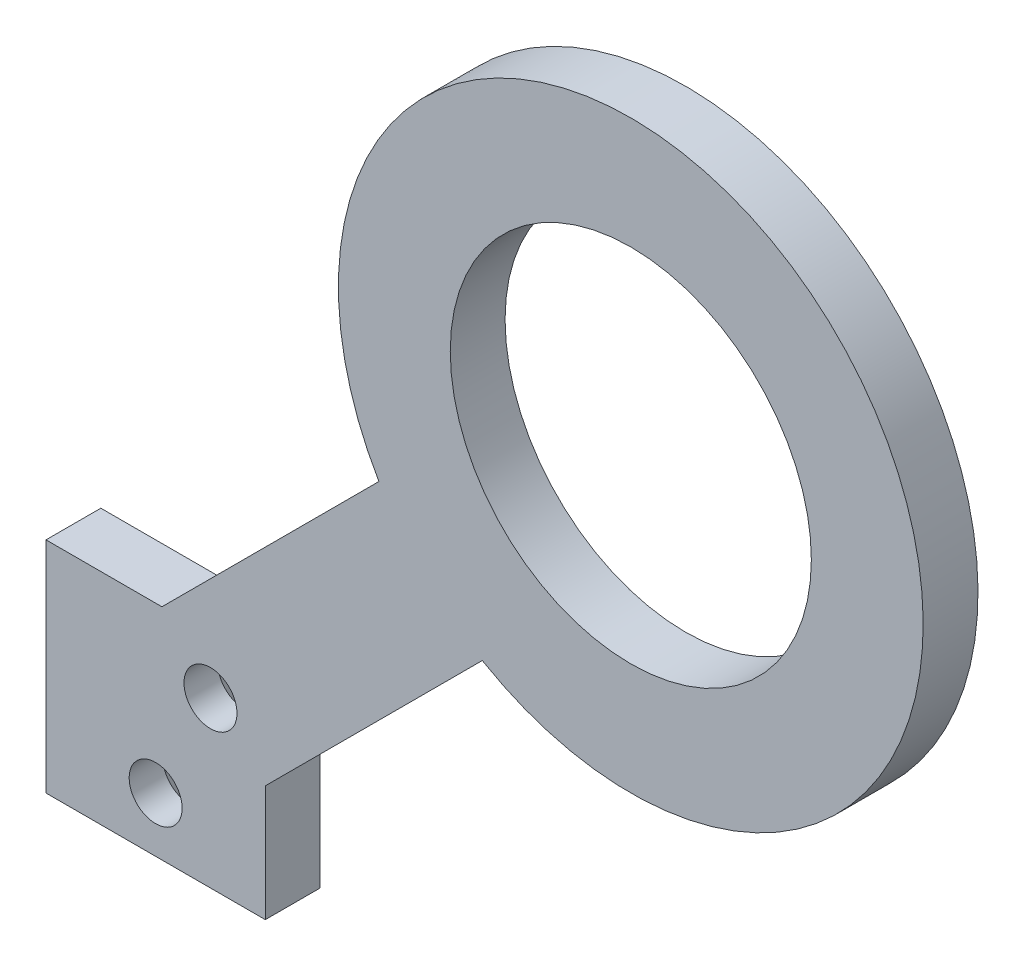
SolidWorks part; units mm, degrees
ref_plane "Front Plane" through (0, 0, 0) normal (0, 0, 1) x (1, 0, 0)
ref_plane "Top Plane" through (0, 0, 0) normal (0, 1, 0) x (1, 0, 0)
ref_plane "Right Plane" through (0, 0, 0) normal (1, 0, 0) x (0, 0, -1)
sketch "Sketch1" plane through (0, 0, 0) normal (0, 0, 1) x (1, 0, 0)
  circle A0 centre (50, 50) radius 16
  circle A1 centre (50, 50) radius 9.88
extrude "Stop_Ring_D19p76_OD32" add sketch "Sketch1" along normal blind 3 from offset 3
sketch "Sketch2" plane through (0, 0, 0) normal (0, 0, 1) x (1, 0, 0)
  line L0 (21.1716, 26.8284) -> (37.6716, 43.3284)
  line L1 (37.6716, 43.3284) -> (43.3284, 37.6716)
  line L2 (43.3284, 37.6716) -> (26.8284, 21.1716)
  line L3 (26.8284, 21.1716) -> (21.1716, 26.8284)
extrude "Outboard_Bridge" add sketch "Sketch2" along normal blind 3 from offset 3
sketch "Sketch3" plane through (0, 0, 0) normal (0, 0, 1) x (1, 0, 0)
  line L1 (18, 18) -> (30, 18)
  line L2 (18, 18) -> (18, 30)
  line L3 (18, 30) -> (30, 30)
  line L4 (30, 18) -> (30, 30)
extrude "Base_Attachment_Pad" add sketch "Sketch3" along normal blind 3 from offset 3
sketch "Sketch5" plane through (0, 0, -3) normal (0, 0, -1) x (-1, 0, 0)
  circle A0 centre (-21, 21) radius 1.45
  circle A1 centre (-27, 27) radius 1.45
sketch "Sketch6" plane through (0, 0, -3) normal (0, 0, -1) x (-1, 0, 0)
  circle A0 centre (-21, 21) radius 2.6
  circle A1 centre (-27, 27) radius 2.6
sketch "Sketch7" plane through (0, 0, -3) normal (0, 0, -1) x (-1, 0, 0)
  circle A0 centre (-21, 21) radius 2.6
  circle A1 centre (-27, 27) radius 2.6
sketch "Sketch8" plane through (0, 0, -3) normal (0, 0, -1) x (-1, 0, 0)
  circle A0 centre (-24, 21) radius 1.45
  circle A1 centre (-27, 27) radius 1.45
extrude "Stop_Mount_D2p9_Through" cut sketch "Sketch8" against normal blind 3.01
sketch "Sketch9" plane through (0, 0, -3) normal (0, 0, -1) x (-1, 0, 0)
  circle A0 centre (-24, 21) radius 2.6
  circle A1 centre (-27, 27) radius 2.6
extrude "Stop_Mount_CSK_D5p2_90deg" cut sketch "Sketch9" against normal blind 1.15 draft 45
